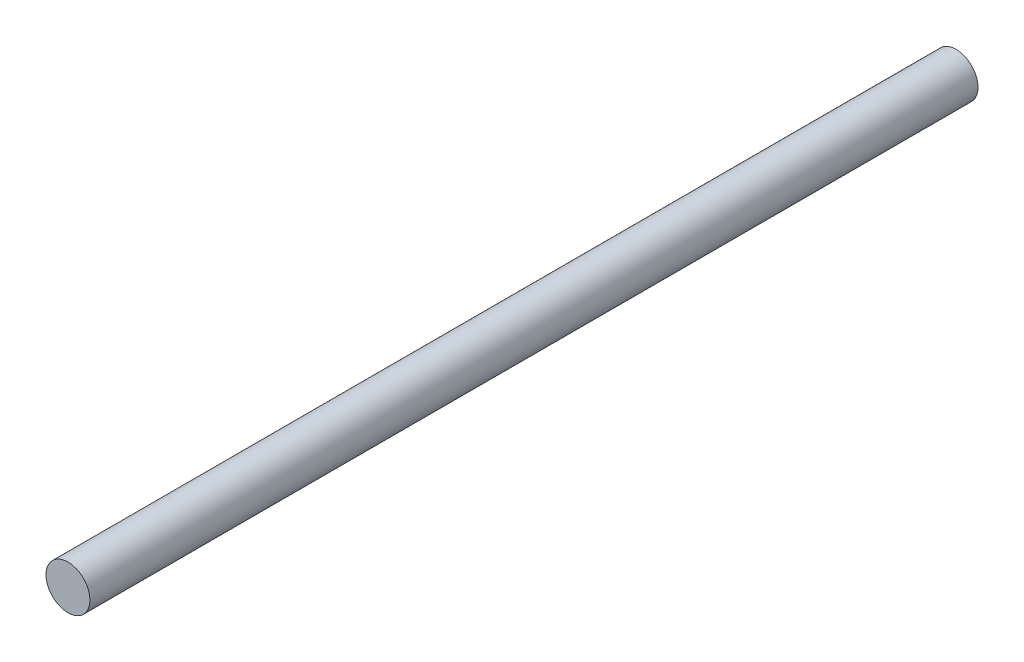
SolidWorks part; units mm, degrees
ref_plane "Front Plane" through (0, 0, 0) normal (0, 0, 1) x (1, 0, 0)
ref_plane "Top Plane" through (0, 0, 0) normal (0, 1, 0) x (1, 0, 0)
ref_plane "Right Plane" through (0, 0, 0) normal (1, 0, 0) x (0, 0, -1)
sketch "Sketch1" plane through (0, 0, 0) normal (0, 0, 1) x (1, 0, 0)
  circle A0 centre (0, 0) radius 2.5
  dimension "D1" = 5
extrude "Boss-Extrude1" add sketch "Sketch1" along normal blind 101.12
